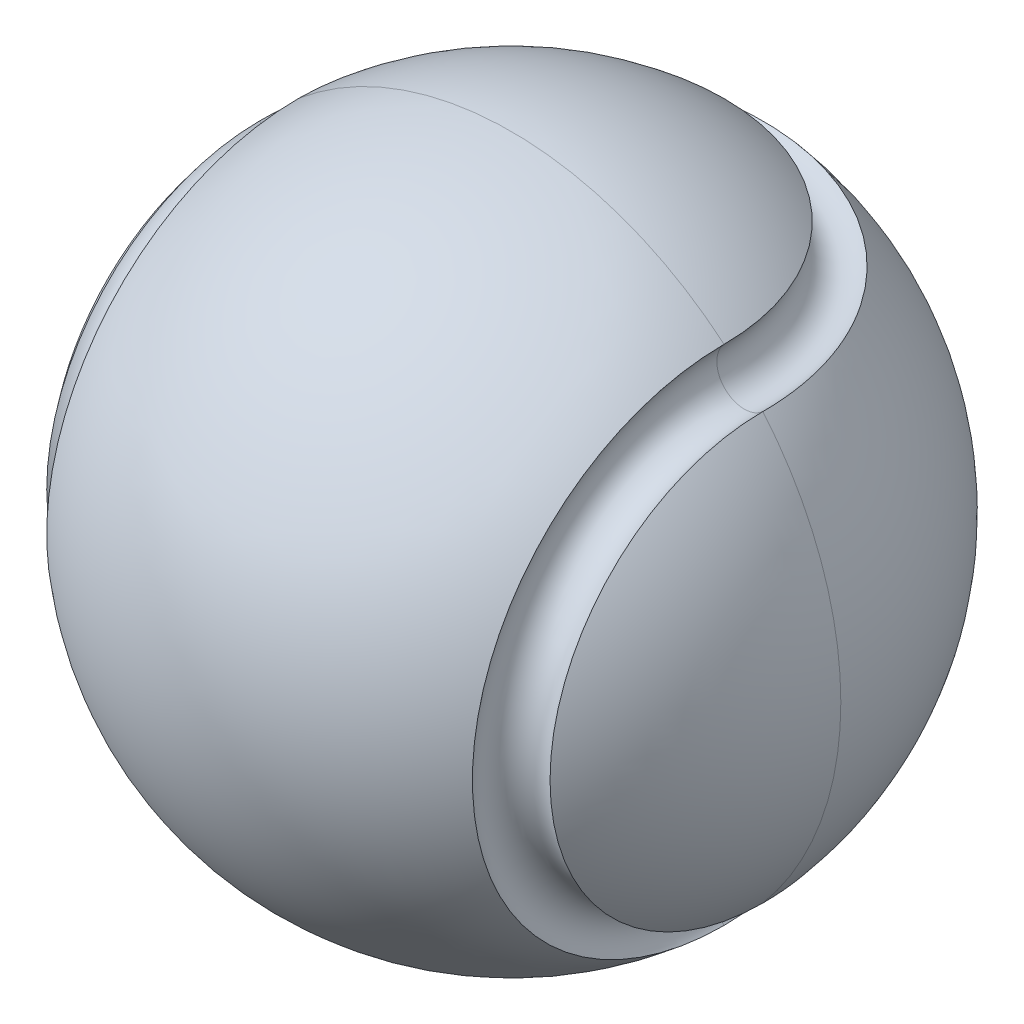
SolidWorks part; units mm, degrees
ref_plane "Front Plane" through (0, 0, 0) normal (0, 0, 1) x (1, 0, 0)
ref_plane "Top Plane" through (0, 0, 0) normal (0, 1, 0) x (1, 0, 0)
ref_plane "Right Plane" through (0, 0, 0) normal (1, 0, 0) x (0, 0, -1)
sketch "Sketch1" plane through (0, 0, 0) normal (0, 0, 1) x (1, 0, 0)
  line L0 (-76.2, 0) -> (76.2, 0)
  arc A0 (-76.2, 0) -> (76.2, 0) centre (0, 0) cw
  point P4 (0, 0)
  dimension "D1" = 152.4
  dimension "D2" = 76.2
revolve "Revolve1" add sketch "Sketch1" angle 360 about L0
sketch "Sketch2" plane through (0, 0, 0) normal (0, 0, 1) x (1, 0, 0)
  line L1 (-53.8815, -53.8815) -> (53.8815, -53.8815)
  line L2 (-53.8815, -53.8815) -> (-53.8815, 53.8815) construction
  line L3 (-53.8815, 53.8815) -> (53.8815, 53.8815) construction
  line L4 (53.8815, -53.8815) -> (53.8815, 53.8815) construction
  line L5 (-53.8815, -53.8815) -> (53.8815, 53.8815) construction
  line L6 (-53.8815, 53.8815) -> (53.8815, -53.8815) construction
  circle A0 centre (0, 0) radius 76.2 construction
  circle A1 centre (0, 0) radius 76.2
  point P7 (0, 0)
  point P8 (0, 0)
  point P9 (0, 0)
  point P10 (0, 0)
  point P11 (-53.8815, 0)
split line "Split Line1"
sketch "Sketch4" plane through (0, 0, 0) normal (0, 0, 1) x (1, 0, 0)
  line L0 (-53.8815, -53.8815) -> (-53.8815, 53.8815) construction
  line L1 (-53.8815, -53.8815) -> (-53.8815, 53.8815)
curve "Curve5"
sketch "Sketch5" plane through (0, 0, 0) normal (0, 0, 1) x (1, 0, 0)
  line L0 (-53.8815, 53.8815) -> (53.8815, 53.8815) construction
  line L1 (-53.8815, 53.8815) -> (53.8815, 53.8815)
split line "Split Line2"
sketch "Sketch7" plane through (0, 0, 0) normal (0, 0, 1) x (1, 0, 0)
  line L0 (53.8815, -53.8815) -> (53.8815, 53.8815) construction
  line L1 (53.8815, -53.8815) -> (53.8815, 53.8815)
curve "Curve7"
curve "CompCurve1"
sweep "Cut-Sweep1" cut path "CompCurve1" circular profile diameter 12.7 parameters "D3"=12.7
